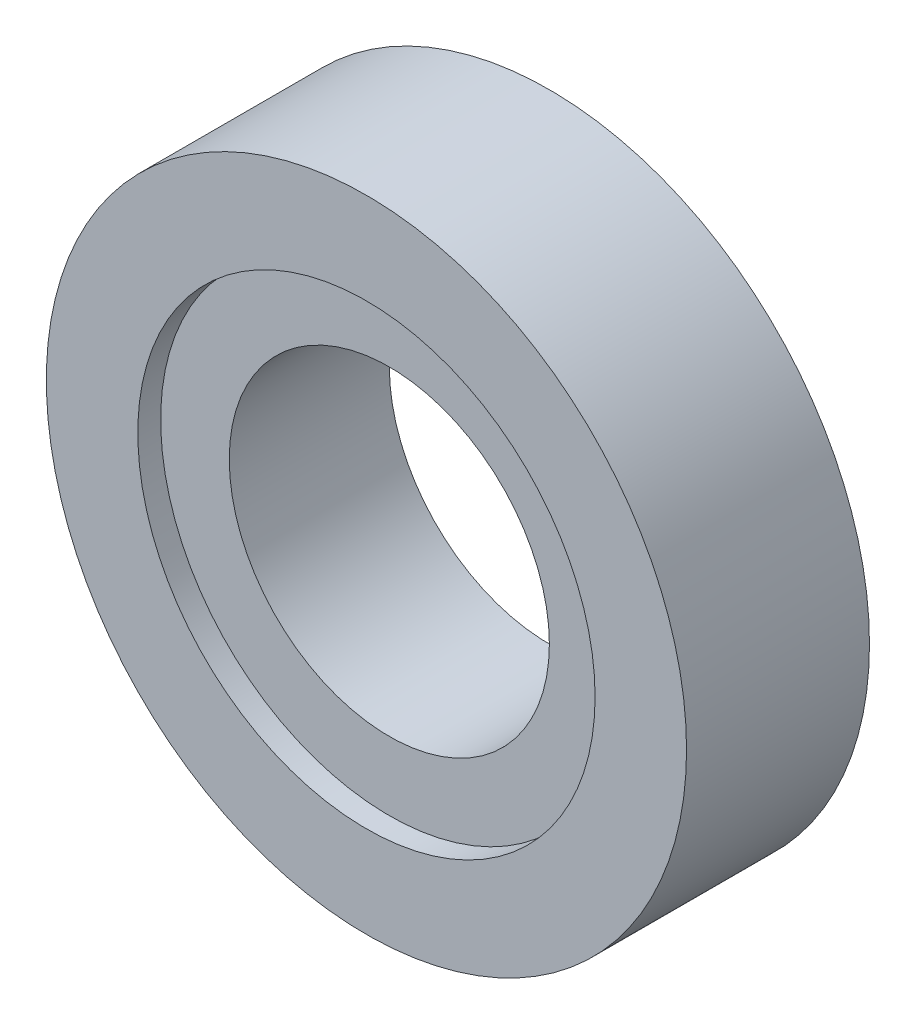
SolidWorks part; units mm, degrees
ref_plane "Front Plane" through (0, 0, 0) normal (0, 0, 1) x (1, 0, 0)
ref_plane "Top Plane" through (0, 0, 0) normal (0, 1, 0) x (1, 0, 0)
ref_plane "Right Plane" through (0, 0, 0) normal (1, 0, 0) x (0, 0, -1)
sketch "Sketch1" plane through (0, 0, 0) normal (0, 0, 1) x (1, 0, 0)
  circle A0 centre (0, 0) radius 7
  circle A1 centre (0, 0) radius 3.5
  dimension "D1" = 14
  dimension "D2" = 7
extrude "Boss-Extrude1" add sketch "Sketch1" along normal blind 4
sketch "Sketch2" plane through (0, 0, 4) normal (0, 0, 1) x (1, 0, 0)
  circle A2 centre (0, 0) radius 3.5 construction
  circle A3 centre (0, 0) radius 5
  circle A4 centre (0, 0) radius 5
  circle A5 centre (0, 0) radius 3.5
  dimension "D1" = 2
extrude "Cut-Extrude1" cut sketch "Sketch2" against normal blind 0.5
